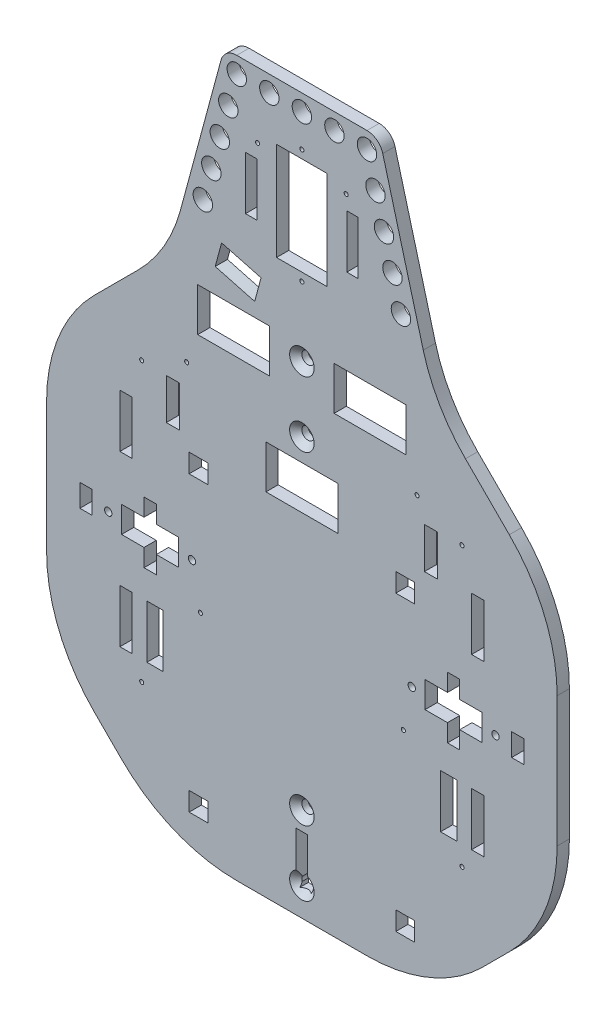
SolidWorks part; units mm, degrees
other "Popis1"
sketch "Skica4" plane through (-62.5, 107.5, 3) normal (-0.0791, 0.0312, 0.9964) x (0.9969, 0.0058, 0.079)
sketch "Skica5" plane through (-62.5, 107.5, 3) normal (-0.0791, 0.0312, 0.9964) x (0.9969, 0.0058, 0.079)
sketch "Skica6" plane through (-62.5, 112.5, 3) normal (-0.0791, 0.0312, 0.9964) x (0.9969, 0.0058, 0.079)
sketch "Skica7" plane through (-62.5, 112.5, 3) normal (-0.0791, 0.0312, 0.9964) x (0.9969, 0.0058, 0.079)
sketch "Skica8" plane through (-62.5, 112.5, 3) normal (-0.0791, 0.0312, 0.9964) x (0.9969, 0.0058, 0.079)
sketch "Skica9" plane through (-62.5, 112.5, 3) normal (-0.0791, 0.0312, 0.9964) x (0.9969, 0.0058, 0.079)
sketch "Skica15" plane through (-62.5, 112.5, 3) normal (-0.0791, 0.0312, 0.9964) x (0.9969, 0.0058, 0.079)
ref_plane "Přední rovina" through (0, 0, 0) normal (0, 0, 1) x (1, 0, 0)
ref_plane "Horní rovina" through (0, 0, 0) normal (0, 1, 0) x (1, 0, 0)
ref_plane "Pravá rovina" through (0, 0, 0) normal (1, 0, 0) x (0, 0, -1)
sketch "Skica1" plane through (0, 0, 0) normal (0, 0, 1) x (1, 0, 0)
  line L0 (-334.3708, 0) -> (16384.1714, 0) construction
  line L1 (0, -334.3708) -> (0, 16384.1714) construction
  line L2 (-44.3956, 7.5) -> (-44.3956, -7.5) construction
  line L3 (-62.5, -62.5) -> (62.5, -62.5) construction
  line L4 (-62.5, -62.5) -> (-62.5, 62.5) construction
  line L5 (-62.5, 62.5) -> (62.5, 62.5) construction
  line L6 (62.5, -62.5) -> (62.5, 62.5) construction
  line L7 (-62.5, -62.5) -> (62.5, 62.5) construction
  line L8 (-62.5, 62.5) -> (62.5, -62.5) construction
  line L9 (-44.3956, 7.5) -> (-61.3, 7.5) construction
  line L10 (-41.5478, 0) -> (-41.5478, 14.2) construction
  line L11 (-44.1478, 3.2) -> (-38.6478, 3.2)
  line L13 (-44.5478, 27.2) -> (-41.5478, 27.2)
  line L14 (-44.5478, 27.2) -> (-44.5478, 14.2)
  line L15 (-44.5478, 14.2) -> (-41.5478, 14.2)
  line L16 (-41.5478, 27.2) -> (-41.5478, 14.2)
  line L20 (-54.3478, 2.75) -> (-51.3478, 2.75)
  line L21 (-54.3478, 2.75) -> (-54.3478, -2.75)
  line L22 (-54.3478, -2.75) -> (-51.3478, -2.75)
  line L23 (-51.3478, 2.75) -> (-51.3478, -2.75)
  line L24 (-54.3478, 2.75) -> (-51.3478, -2.75) construction
  line L25 (-54.3478, -2.75) -> (-51.3478, 2.75) construction
  line L26 (-44.1478, 3.2) -> (-30.1478, 3.2) construction
  line L27 (-44.1478, 3.2) -> (-44.1478, -3.2)
  line L28 (-44.1478, -3.2) -> (-30.1478, -3.2) construction
  line L29 (-30.1478, 3.2) -> (-30.1478, -3.2)
  line L30 (-44.1478, 3.2) -> (-30.1478, -3.2) construction
  line L31 (-44.1478, -3.2) -> (-30.1478, 3.2) construction
  line L32 (-38.6478, -7.5) -> (-35.6478, -7.5)
  line L33 (-38.6478, -7.5) -> (-38.6478, 7.5) construction
  line L34 (-38.6478, 7.5) -> (-35.6478, 7.5)
  line L35 (-35.6478, -7.5) -> (-35.6478, 7.5) construction
  line L36 (-38.6478, -7.5) -> (-35.6478, 7.5) construction
  line L37 (-38.6478, 7.5) -> (-35.6478, -7.5) construction
  line L38 (-38.6478, 3.2) -> (-38.6478, 7.5)
  line L39 (-35.6478, 7.5) -> (-35.6478, 3.2)
  line L40 (-35.6478, 3.2) -> (-30.1478, 3.2)
  line L41 (-30.1478, -3.2) -> (-35.6478, -3.2)
  line L42 (-35.6478, -3.2) -> (-35.6478, -7.5)
  line L43 (-38.6478, -7.5) -> (-38.6478, -3.2)
  line L44 (-38.6478, -3.2) -> (-44.1478, -3.2)
  line L45 (-41.5478, -27.2) -> (-41.5478, -14.2)
  line L46 (-44.5478, -27.2) -> (-41.5478, -27.2)
  line L47 (-44.5478, -27.2) -> (-44.5478, -14.2)
  line L48 (-44.5478, -14.2) -> (-41.5478, -14.2)
  line L49 (-62.5, -32.5) -> (-62.5, 32.5)
  line L50 (-62.5, 32.5) -> (-32.5, 62.5)
  line L51 (-62.5, -32.5) -> (-32.5, -62.5)
  line L52 (-32.5, -62.5) -> (32.5, -62.5)
  line L54 (38.6478, -7.5) -> (35.6478, -7.5)
  line L55 (38.6478, -7.5) -> (38.6478, -3.2)
  line L56 (35.6478, -3.2) -> (35.6478, -7.5)
  line L57 (30.1478, -3.2) -> (35.6478, -3.2)
  line L58 (38.6478, -3.2) -> (44.1478, -3.2)
  line L59 (30.1478, 3.2) -> (30.1478, -3.2)
  line L60 (35.6478, 3.2) -> (30.1478, 3.2)
  line L61 (38.6478, 7.5) -> (35.6478, 7.5)
  line L62 (35.6478, 7.5) -> (35.6478, 3.2)
  line L63 (38.6478, 3.2) -> (38.6478, 7.5)
  line L64 (44.1478, 3.2) -> (44.1478, -3.2)
  line L65 (44.1478, 3.2) -> (38.6478, 3.2)
  line L66 (51.3478, 2.75) -> (51.3478, -2.75)
  line L67 (54.3478, -2.75) -> (51.3478, -2.75)
  line L68 (54.3478, 2.75) -> (54.3478, -2.75)
  line L69 (54.3478, 2.75) -> (51.3478, 2.75)
  line L70 (41.5478, 27.2) -> (41.5478, 14.2)
  line L71 (44.5478, 14.2) -> (41.5478, 14.2)
  line L72 (44.5478, 27.2) -> (44.5478, 14.2)
  line L73 (44.5478, 27.2) -> (41.5478, 27.2)
  line L74 (44.5478, -14.2) -> (41.5478, -14.2)
  line L75 (44.5478, -27.2) -> (44.5478, -14.2)
  line L76 (44.5478, -27.2) -> (41.5478, -27.2)
  line L77 (41.5478, -27.2) -> (41.5478, -14.2)
  line L78 (62.5, -32.5) -> (32.5, -62.5)
  line L79 (62.5, -32.5) -> (62.5, 32.5)
  line L80 (62.5, 32.5) -> (32.5, 62.5)
  line L81 (25.5, 59.1) -> (25.5, 48.5)
  line L82 (-8.8, 34.1) -> (8.8, 34.1)
  line L83 (-8.8, 34.1) -> (-8.8, 23.5)
  line L84 (-8.8, 23.5) -> (8.8, 23.5)
  line L85 (8.8, 34.1) -> (8.8, 23.5)
  line L86 (-8.8, 34.1) -> (8.8, 23.5) construction
  line L87 (-8.8, 23.5) -> (8.8, 34.1) construction
  line L88 (-25.5, 59.1) -> (-7.9, 59.1)
  line L89 (-25.5, 59.1) -> (-25.5, 48.5)
  line L90 (-25.5, 48.5) -> (-7.9, 48.5)
  line L91 (-7.9, 59.1) -> (-7.9, 48.5)
  line L92 (7.9, 59.1) -> (7.9, 48.5)
  line L93 (25.5, 48.5) -> (7.9, 48.5)
  line L94 (25.5, 59.1) -> (7.9, 59.1)
  line L95 (-6.2, 74.5) -> (-6.2, 98.5)
  line L96 (-6.2, 98.5) -> (6.2, 98.5)
  line L97 (6.2, 98.5) -> (6.2, 74.5)
  line L98 (6.2, 74.5) -> (-6.2, 74.5)
  line L99 (-11, 93) -> (-11, 80)
  line L100 (-11, 80) -> (-13.8, 80)
  line L101 (-13.8, 80) -> (-13.8, 93)
  line L102 (-13.8, 93) -> (-11, 93)
  line L107 (-21.2122, 65.0882) -> (-11.5529, 62.5)
  line L108 (-11.5529, 62.5) -> (-10, 68.2956)
  line L109 (-10, 68.2956) -> (-19.6593, 70.8837)
  line L110 (-19.6593, 70.8837) -> (-21.2122, 65.0882)
  line L111 (-6.2, 86.5) -> (6.2, 86.5) construction
  line L112 (-6.2, 86.5) -> (-11, 86.5) construction
  line L113 (11, 80) -> (13.8, 80)
  line L114 (11, 93) -> (11, 80)
  line L115 (13.8, 93) -> (11, 93)
  line L116 (13.8, 80) -> (13.8, 93)
  line L117 (30, 26) -> (33.2, 26)
  line L118 (-30, 36) -> (-33.2, 36)
  line L119 (-30, 36) -> (-30, 26)
  line L120 (-30, 26) -> (-33.2, 26)
  line L121 (-33.2, 36) -> (-33.2, 26)
  line L122 (33.2, 36) -> (33.2, 26)
  line L123 (30, 36) -> (33.2, 36)
  line L124 (30, 36) -> (30, 26)
  line L125 (-32.5, 62.5) -> (-19.0034, 112.5)
  line L126 (-19.0034, 112.5) -> (19.0034, 112.5)
  line L129 (0, 108.5) -> (7.97, 108.5) construction
  line L137 (32.5, 62.5) -> (19.0034, 112.5)
  line L138 (-15.94, 108.5) -> (-28.3568, 62.5) construction
  line L140 (-25.3, -51.5) -> (25.3, -51.5) construction
  line L141 (-25.3, -51.5) -> (-25.3, 20.23) construction
  line L142 (-25.3, 20.23) -> (25.3, 20.23) construction
  line L143 (25.3, -51.5) -> (25.3, 20.23) construction
  line L144 (-25.3, -51.5) -> (25.3, 20.23) construction
  line L145 (-25.3, 20.23) -> (25.3, -51.5) construction
  line L146 (-25.3, -15.635) -> (25.3, -15.635) construction
  line L147 (23, 22.53) -> (27.6, 22.53)
  line L148 (23, 22.53) -> (23, 17.93)
  line L149 (23, 17.93) -> (27.6, 17.93)
  line L150 (27.6, 22.53) -> (27.6, 17.93)
  line L151 (23, 22.53) -> (27.6, 17.93) construction
  line L152 (23, 17.93) -> (27.6, 22.53) construction
  line L153 (23, -49.2) -> (27.6, -49.2)
  line L154 (27.6, -53.8) -> (27.6, -49.2)
  line L155 (23, -53.8) -> (27.6, -53.8)
  line L156 (23, -53.8) -> (23, -49.2)
  line L157 (-23, -53.8) -> (-27.6, -53.8)
  line L158 (-23, -53.8) -> (-23, -49.2)
  line L159 (-27.6, -53.8) -> (-27.6, -49.2)
  line L160 (-23, -49.2) -> (-27.6, -49.2)
  line L161 (-23, 22.53) -> (-23, 17.93)
  line L162 (-23, 22.53) -> (-27.6, 22.53)
  line L163 (-27.6, 22.53) -> (-27.6, 17.93)
  line L164 (-23, 17.93) -> (-27.6, 17.93)
  line L165 (37.1478, 7.5) -> (37.1478, -7.5) construction
  circle A0 centre (-52.8478, 0) radius 11.3 construction
  circle A1 centre (0, 100.5) radius 0.5
  circle A3 centre (0, 72.5) radius 0.5
  circle A4 centre (0, 108.5) radius 2.375
  circle A5 centre (7.97, 108.5) radius 2.375
  circle A6 centre (15.94, 108.5) radius 2.375
  circle A7 centre (-15.94, 108.5) radius 2.375
  circle A8 centre (-7.97, 108.5) radius 2.375
  circle A9 centre (-15.94, 108.5) radius 2.375 construction
  circle A10 centre (-18.017, 100.8054) radius 2.375
  circle A11 centre (-20.094, 93.1108) radius 2.375
  circle A12 centre (-22.171, 85.4162) radius 2.375
  circle A13 centre (-24.2481, 77.7216) radius 2.375
  circle A14 centre (24.2481, 77.7216) radius 2.375
  circle A15 centre (22.171, 85.4162) radius 2.375
  circle A16 centre (20.094, 93.1108) radius 2.375
  circle A17 centre (18.017, 100.8054) radius 2.375
  circle A18 centre (47.3978, 0) radius 0.9
  circle A19 centre (26.8978, 0) radius 0.9
  circle A20 centre (-47.3978, 0) radius 0.9
  circle A21 centre (-26.8978, 0) radius 0.9
  point P4 (0, 0)
  point P15 (-52.8478, 0)
  point P17 (-37.1478, 0)
  point P27 (-37.1478, 0)
  point P46 (52.8478, 0)
  point P48 (0, 28.8)
  point P49 (0, -62.5)
  point P78 (0, 62.5)
  point P138 (0, 112.5)
  point P149 (-15.94, 108.5)
  point P156 (0, -15.635)
  dimension "D3" = 13
  dimension "D6" = 22.6
  dimension "D30" = 1
  dimension "D40" = 4.75
  dimension "D44" = 4
  dimension "D53" = 1.8
  dimension "D1" = 125
  dimension "D2" = 125
  dimension "D4" = 3
  dimension "D5" = 14.2
  dimension "D7" = 15
  dimension "D8" = 1.2
  dimension "D9" = 3
  dimension "D10" = 5.5
  dimension "D11" = 6.8
  dimension "D12" = 14
  dimension "D13" = 6.4
  dimension "D14" = 3
  dimension "D15" = 15
  dimension "D17" = 65
  dimension "D18" = 45
  dimension "D19" = 86
  dimension "D20" = 17.6
  dimension "D21" = 10.6
  dimension "D22" = 7.9
  dimension "D23" = 14.4
  dimension "D24" = 12.4
  dimension "D25" = 24
  dimension "D26" = 13
  dimension "D27" = 2.8
  dimension "D28" = 11
  dimension "D29" = 12
  dimension "D31" = 2
  dimension "D32" = 10
  dimension "D33" = 6
  dimension "D34" = 10
  dimension "D35" = 15
  dimension "D36" = 3.2
  dimension "D37" = 10
  dimension "D38" = 30
  dimension "D39" = 26
  dimension "D42" = 7.97
  dimension "D43" = 4
  dimension "D45" = 8
  dimension "D46" = 74.894
  dimension "D47" = 2
  dimension "D48" = 71.73
  dimension "D49" = 50.6
  dimension "D50" = 11
  dimension "D51" = 4.6
  dimension "D52" = 10.25
  dimension "D54" = 14.2
  dimension "D41" = 3
extrude "Přidat vysunutím1" add sketch "Skica1" along normal blind 3
sketch "Skica2" plane through (0, 0, 0) normal (0, 0, 1) x (1, 0, 0)
  line L0 (0, -1000) -> (0, 49000) construction
  line L1 (-1000, 0) -> (49000, 0) construction
  line L2 (8.8, 34.1) -> (-8.8, 34.1) construction
  circle A0 centre (0, 39.6) radius 1.5
  circle A1 centre (0, 55.6) radius 1.5
  circle A2 centre (0, -55.6) radius 1.5
  circle A3 centre (0, -39.6) radius 1.5
  dimension "D3" = 3
  dimension "D1" = 5.5
  dimension "D2" = 16
extrude "Odebrat vysunutím1" cut sketch "Skica2" along normal up to surface (3 mm away) up to face at (-25.3, -51.5, 3)
chamfer "Zkosení1" distance 1.5 angle 45 4 edges at (-1.5, -55.6, 3) (-1.5, -39.6, 3) (-1.5, 39.6, 3) (-1.5, 55.6, 3)
fillet "Zaoblit1" radius 40 8 edges at (-62.5, -32.5, 1.5) (-32.5, -62.5, 1.5) (32.5, -62.5, 1.5) (62.5, -32.5, 1.5) (62.5, 32.5, 1.5) (-62.5, 32.5, 1.5) (32.5, 62.5, 1.5) (-32.5, 62.5, 1.5)
fillet "Zaoblit2" radius 4 2 edges at (19.0034, 112.5, 1.5) (-19.0034, 112.5, 1.5)
sketch "Skica3" plane through (0, 0, 3) normal (0, 0, 1) x (1, 0, 0)
  line L0 (0, -965.9) -> (0, 49034.1) construction
  line L1 (8.8, 34.1) -> (-8.8, 34.1) construction
  line L2 (-11, 93) -> (-13.8, 93) construction
  line L3 (-1.4, -44.1) -> (1.4, -44.1)
  line L4 (-1.4, -44.1) -> (-1.4, -57.1)
  line L5 (-1.4, -57.1) -> (1.4, -57.1)
  line L6 (1.4, -44.1) -> (1.4, -57.1)
  line L7 (-13.8, 93) -> (-13.8, 80) construction
  circle A0 centre (-28.2, 41.3) radius 0.5
  circle A1 centre (28.2, 41.3) radius 0.5
  circle A2 centre (0, -55.6) radius 1.5 construction
  point P5 (0, 34.1)
  dimension "D1" = 1
  dimension "D2" = 28.2
  dimension "D3" = 7.2
extrude "Odebrat vysunutím2" cut sketch "Skica3" against normal through all
sketch "Skica11" plane through (0, 0, 3) normal (0, 0, 1) x (1, 0, 0)
  circle A0 centre (-37.9664, 35.4369) radius 0.5
sketch "Skica12" plane through (0, 0, 3) normal (0, 0, 1) x (1, 0, 0)
  line L0 (0, -62.5) -> (0, 160.436) construction
  line L1 (-15.9315, -62.5) -> (15.9315, -62.5) construction
  circle A0 centre (10.8484, 96.4635) radius 0.5
  circle A1 centre (39.2142, 36.2032) radius 0.5
  circle A2 centre (39.2142, -31.993) radius 0.5
  circle A3 centre (24.8426, -10.1597) radius 0.5
  circle A4 centre (-39.2142, -31.993) radius 0.5
  circle A5 centre (-39.2142, 36.2032) radius 0.5
extrude "Odebrat vysunutím3" cut sketch "Skica12" against normal blind 10
sketch "Skica13" plane through (0, 0, 3) normal (0, 0, 1) x (1, 0, 0)
  line L0 (0, -72.6699) -> (0, 212.348) construction
  line L1 (37.9439, -27.2) -> (33.9439, -27.2)
  line L2 (-37.9439, -27.2) -> (-33.9439, -27.2)
  line L3 (-37.9439, -27.2) -> (-37.9439, -14.2)
  line L4 (-37.9439, -14.2) -> (-33.9439, -14.2)
  line L5 (-33.9439, -27.2) -> (-33.9439, -14.2)
  line L6 (37.9439, -27.2) -> (37.9439, -14.2)
  line L7 (37.9439, -14.2) -> (33.9439, -14.2)
  line L8 (33.9439, -27.2) -> (33.9439, -14.2)
  dimension "D1" = 13
  dimension "D2" = 4
sketch "Skica14" plane through (0, 0, 3) normal (0, 0, 1) x (1, 0, 0)
  circle A0 centre (-10.8484, 96.4635) radius 0.5
  circle A1 centre (-24.8426, -10.1597) radius 0.5
extrude "Odebrat vysunutím5" cut sketch "Skica14" against normal blind 10
extrude "Odebrat vysunutím6" cut sketch "Skica13" against normal blind 10
